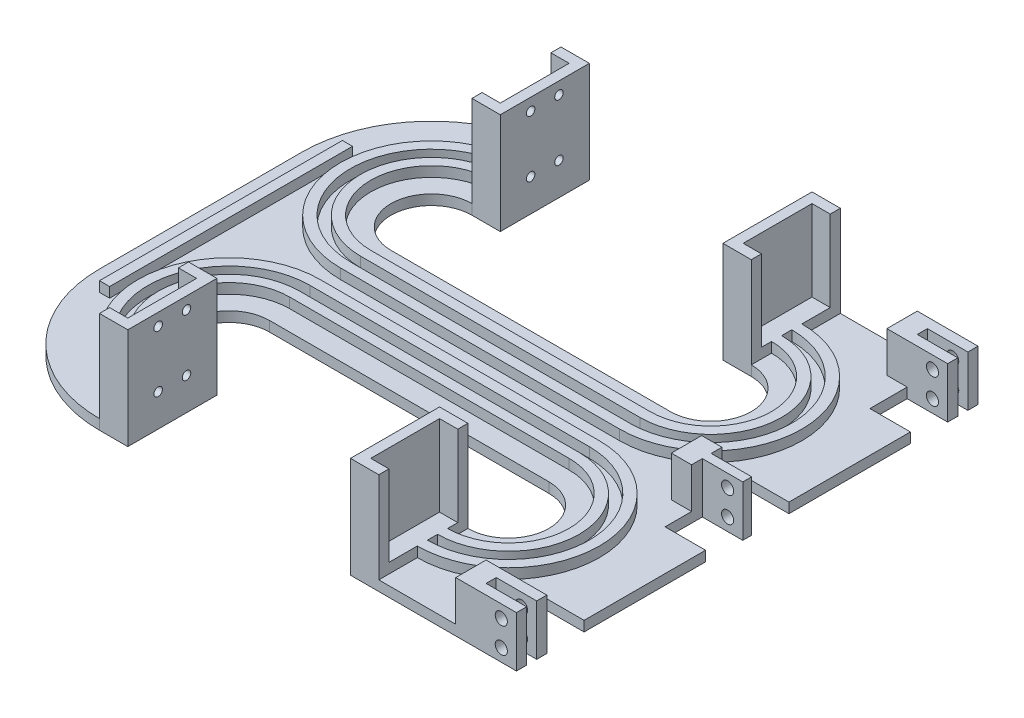
SolidWorks part; units mm, degrees
ref_plane "Front Plane" through (0, 0, 0) normal (0, 0, 1) x (1, 0, 0)
ref_plane "Top Plane" through (0, 0, 0) normal (0, 1, 0) x (1, 0, 0)
ref_plane "Right Plane" through (0, 0, 0) normal (1, 0, 0) x (0, 0, -1)
sketch "Sketch1" plane through (0, 0, 0) normal (0, 1, 0) x (1, 0, 0)
  line L5 (-62.5, 25) -> (-62.5, -25)
  line L6 (-30.5, -15) -> (38.5, -15)
  line L7 (38.5, -57) -> (62.5, -57)
  line L8 (62.5, -57) -> (62.5, 57)
  line L10 (-30.5, -57) -> (-30.5, 57) construction
  line L11 (-30.5, -35) -> (-23.5, -35)
  line L14 (-30.5, -57) -> (-23.5, -57)
  line L15 (-23.5, -35) -> (-23.5, -57)
  line L16 (38.5, -35) -> (31.5, -35)
  line L18 (38.5, -57) -> (31.5, -57)
  line L19 (31.5, -35) -> (31.5, -57)
  line L20 (38.5, -57) -> (38.5, 57) construction
  line L21 (-62.5, -25) -> (62.5, -25) construction
  line L22 (-62.5, 0) -> (62.5, 0) construction
  line L23 (-62.5, 25) -> (62.5, 25) construction
  line L24 (31.5, 35) -> (31.5, 57)
  line L25 (38.5, 57) -> (31.5, 57)
  line L26 (38.5, 35) -> (31.5, 35)
  line L27 (-23.5, 35) -> (-23.5, 57)
  line L28 (-30.5, 57) -> (-23.5, 57)
  line L29 (-30.5, 35) -> (-23.5, 35)
  line L30 (38.5, 57) -> (62.5, 57)
  line L31 (-30.5, 15) -> (38.5, 15)
  arc A0 (-62.5, -25) -> (-30.5, -57) centre (-30.5, -25) ccw
  arc A1 (-30.5, -15) -> (-30.5, -35) centre (-30.5, -25) ccw
  arc A2 (38.5, -15) -> (38.5, -35) centre (38.5, -25) cw
  arc A3 (38.5, 15) -> (38.5, 35) centre (38.5, 25) ccw
  arc A4 (-30.5, 15) -> (-30.5, 35) centre (-30.5, 25) cw
  arc A5 (-62.5, 25) -> (-30.5, 57) centre (-30.5, 25) cw
  point P23 (38.5, 0)
  point P24 (-30.5, 0)
  point P35 (0, 0)
  dimension "D2" = 10
  dimension "D1" = 25
  dimension "D3" = 22
  dimension "D4" = 7
  dimension "D5" = 55
  dimension "D6" = 125
extrude "Boss-Extrude1" add sketch "Sketch1" along normal blind 2.5
sketch "Sketch3" plane through (0, 2.5, 0) normal (0, 1, 0) x (1, 0, 0)
  line L0 (0, 0) -> (-62.5, 0) construction
  line L2 (-30.5, -2.5) -> (38.5, -2.5)
  line L3 (-30.5, -5) -> (38.5, -5)
  line L4 (-30.5, -7.5) -> (38.5, -7.5)
  line L5 (-30.5, -10) -> (38.5, -10)
  line L6 (-30.5, -15) -> (38.5, -15) construction
  line L7 (38.5, -35) -> (31.5, -35)
  line L8 (31.5, -35) -> (31.5, -57)
  line L9 (31.5, -57) -> (38.5, -57)
  line L10 (31.5, -57) -> (62.5, -57) construction
  line L11 (38.5, -57) -> (38.5, -47.5)
  line L12 (38.5, -42.5) -> (38.5, -45)
  line L13 (38.5, -35) -> (38.5, -40)
  line L14 (-30.5, -35) -> (-23.5, -35)
  line L15 (-23.5, -35) -> (-23.5, -57)
  line L16 (-23.5, -57) -> (-30.5, -57)
  line L17 (-30.5, -35) -> (-30.5, -40)
  line L18 (-30.5, -42.5) -> (-30.5, -45)
  line L19 (-30.5, -47.5) -> (-30.5, -57)
  line L20 (-62.5, 25) -> (-62.5, -25) construction
  line L21 (-57.5, 30) -> (-55, 30)
  line L23 (-57.5, 30) -> (-57.5, -30)
  line L24 (-57.5, -30) -> (-55, -30)
  line L25 (-55, 30) -> (-55, -30)
  line L26 (-30.5, 47.5) -> (-30.5, 57)
  line L27 (-30.5, 42.5) -> (-30.5, 45)
  line L28 (-30.5, 35) -> (-30.5, 40)
  line L29 (-23.5, 57) -> (-30.5, 57)
  line L30 (-23.5, 35) -> (-23.5, 57)
  line L31 (-30.5, 35) -> (-23.5, 35)
  line L32 (38.5, 35) -> (38.5, 40)
  line L33 (38.5, 42.5) -> (38.5, 45)
  line L34 (38.5, 57) -> (38.5, 47.5)
  line L35 (31.5, 57) -> (38.5, 57)
  line L36 (31.5, 35) -> (31.5, 57)
  line L37 (38.5, 35) -> (31.5, 35)
  line L38 (-30.5, 10) -> (38.5, 10)
  line L39 (-30.5, 7.5) -> (38.5, 7.5)
  line L40 (-30.5, 5) -> (38.5, 5)
  line L41 (-30.5, 2.5) -> (38.5, 2.5)
  arc A0 (38.5, -10) -> (38.5, -40) centre (38.5, -25) cw
  arc A1 (38.5, -7.5) -> (38.5, -42.5) centre (38.5, -25) cw
  arc A2 (38.5, -5) -> (38.5, -45) centre (38.5, -25) cw
  arc A3 (38.5, -2.5) -> (38.5, -47.5) centre (38.5, -25) cw
  arc A4 (-30.5, -10) -> (-30.5, -40) centre (-30.5, -25) ccw
  arc A5 (-30.5, -7.5) -> (-30.5, -42.5) centre (-30.5, -25) ccw
  arc A6 (-30.5, -5) -> (-30.5, -45) centre (-30.5, -25) ccw
  arc A7 (-30.5, -2.5) -> (-30.5, -47.5) centre (-30.5, -25) ccw
  arc A8 (-30.5, 2.5) -> (-30.5, 47.5) centre (-30.5, 25) cw
  arc A9 (-30.5, 5) -> (-30.5, 45) centre (-30.5, 25) cw
  arc A10 (-30.5, 7.5) -> (-30.5, 42.5) centre (-30.5, 25) cw
  arc A11 (-30.5, 10) -> (-30.5, 40) centre (-30.5, 25) cw
  arc A12 (38.5, 2.5) -> (38.5, 47.5) centre (38.5, 25) ccw
  arc A13 (38.5, 5) -> (38.5, 45) centre (38.5, 25) ccw
  arc A14 (38.5, 7.5) -> (38.5, 42.5) centre (38.5, 25) ccw
  arc A15 (38.5, 10) -> (38.5, 40) centre (38.5, 25) ccw
  point P49 (-62.5, 0)
  point P68 (-55, 0)
  point P69 (-57.5, 0)
  dimension "D1" = 2.5
  dimension "D2" = 2.5
  dimension "D3" = 2.5
  dimension "D4" = 5
  dimension "D5" = 30
  dimension "D6" = 2.5
  dimension "D7" = 5
extrude "Boss-Extrude2" add sketch "Sketch3" along normal blind 2.5
sketch "Sketch4" plane through (0, 5, 0) normal (0, 1, 0) x (1, 0, 0)
  line L0 (-30.5, -35) -> (-23.5, -35)
  line L1 (-23.5, -35) -> (-23.5, -57)
  line L2 (-23.5, -57) -> (-30.5, -57)
  line L3 (-30.5, -57) -> (-30.5, -54.5)
  line L4 (-30.5, -47.5) -> (-30.5, -57) construction
  line L5 (-30.5, -54.5) -> (-26, -54.5)
  line L6 (-26, -54.5) -> (-26, -37.5)
  line L7 (-26, -37.5) -> (-30.5, -37.5)
  line L8 (-30.5, -35) -> (-30.5, -40) construction
  line L9 (-30.5, -37.5) -> (-30.5, -35)
  line L10 (38.5, -35) -> (31.5, -35)
  line L11 (31.5, -35) -> (31.5, -57)
  line L12 (31.5, -35) -> (31.5, -57) construction
  line L13 (31.5, -57) -> (38.5, -57)
  line L14 (38.5, -57) -> (38.5, -54.5)
  line L15 (38.5, -57) -> (38.5, -47.5) construction
  line L16 (38.5, -54.5) -> (34, -54.5)
  line L17 (34, -54.5) -> (34, -37.5)
  line L18 (34, -37.5) -> (38.5, -37.5)
  line L19 (38.5, -40) -> (38.5, -35) construction
  line L20 (38.5, -37.5) -> (38.5, -35)
  line L21 (0, 0) -> (-62.5, 0) construction
  line L22 (-62.5, 25) -> (-62.5, -25) construction
  line L23 (38.5, 37.5) -> (38.5, 35)
  line L24 (34, 37.5) -> (38.5, 37.5)
  line L25 (34, 54.5) -> (34, 37.5)
  line L26 (38.5, 54.5) -> (34, 54.5)
  line L27 (38.5, 57) -> (38.5, 54.5)
  line L28 (31.5, 57) -> (38.5, 57)
  line L29 (31.5, 35) -> (31.5, 57)
  line L30 (38.5, 35) -> (31.5, 35)
  line L31 (-30.5, 37.5) -> (-30.5, 35)
  line L32 (-26, 37.5) -> (-30.5, 37.5)
  line L33 (-26, 54.5) -> (-26, 37.5)
  line L34 (-30.5, 54.5) -> (-26, 54.5)
  line L35 (-30.5, 57) -> (-30.5, 54.5)
  line L36 (-23.5, 57) -> (-30.5, 57)
  line L37 (-23.5, 35) -> (-23.5, 57)
  line L38 (-30.5, 35) -> (-23.5, 35)
  dimension "D1" = 2.5
  dimension "D2" = 2.5
  dimension "D3" = 2.5
extrude "Boss-Extrude3" add sketch "Sketch4" along normal blind 20
sketch "Sketch5" plane through (31.5, 0, 0) normal (-1, 0, 0) x (0, 0, 1)
  line L0 (35, 25) -> (57, 25) construction
  line L1 (57, 25) -> (57, 0) construction
  circle A0 centre (46, 12.5) radius 3.75
  point P4 (46, 25)
  point P7 (57, 12.5)
  dimension "D1" = 7.5
extrude "Boss-Extrude4" add sketch "Sketch5" along normal blind 5.5
sketch "Sketch6" plane through (31.5, 0, 0) normal (-1, 0, 0) x (0, 0, 1)
  line L0 (-57, 25) -> (-35, 25) construction
  line L1 (-57, 25) -> (-57, 0) construction
  circle A0 centre (-46, 12.5) radius 3.75
  point P4 (-46, 25)
  point P7 (-57, 12.5)
  dimension "D1" = 7.5
extrude "Boss-Extrude5" add sketch "Sketch6" along normal blind 5.5
sketch "Sketch8" plane through (-23.5, 0, 0) normal (1, 0, 0) x (0, 0, -1)
  line L0 (-35, 12.5) -> (-57, 12.5) construction
  line L1 (-35, 25) -> (-35, 0) construction
  line L2 (-57, 25) -> (-57, 0) construction
  line L3 (-35, 15) -> (-57, 15) construction
  line L4 (-46, 25) -> (-46, 0) construction
  line L5 (-57, 25) -> (-35, 25) construction
  line L6 (-57, 0) -> (-35, 0) construction
  circle A0 centre (-42.5, 22) radius 1.05
  circle A1 centre (-49.5, 22) radius 1.05
  circle A2 centre (-49.5, 8) radius 1.05
  circle A3 centre (-42.5, 8) radius 1.05
  dimension "D1" = 2.1
  dimension "D2" = 2.5
  dimension "D3" = 7
  dimension "D4" = 3.5
extrude "Cut-Extrude1" cut sketch "Sketch8" against normal blind 2.5
sketch "Sketch9" plane through (-23.5, 0, 0) normal (1, 0, 0) x (0, 0, -1)
  line L0 (57, 12.5) -> (35, 12.5) construction
  line L1 (57, 25) -> (57, 0) construction
  line L2 (35, 25) -> (35, 0) construction
  line L3 (46, 25) -> (46, 0) construction
  line L4 (35, 25) -> (57, 25) construction
  line L5 (35, 0) -> (57, 0) construction
  line L6 (57, 15) -> (35, 15) construction
  circle A0 centre (49.5, 22) radius 1.05
  circle A1 centre (42.5, 22) radius 1.05
  circle A2 centre (42.5, 8) radius 1.05
  circle A3 centre (49.5, 8) radius 1.05
  dimension "D2" = 2.1
  dimension "D1" = 2.5
  dimension "D3" = 7
  dimension "D4" = 3.5
extrude "Cut-Extrude2" cut sketch "Sketch9" against normal blind 2.5
sketch "Sketch10" plane through (0, 2.5, 0) normal (0, 1, 0) x (1, 0, 0)
  line L0 (62.5, -57) -> (62.5, 57) construction
  line L1 (62.5, 57) -> (57.5, 57)
  line L2 (62.5, 57) -> (62.5, 49.5)
  line L3 (62.5, 49.5) -> (57.5, 49.5)
  line L4 (57.5, 57) -> (57.5, 49.5)
  line L5 (62.5, 3.75) -> (57.5, 3.75)
  line L6 (62.5, 3.75) -> (62.5, -3.75)
  line L7 (62.5, -3.75) -> (57.5, -3.75)
  line L8 (57.5, 3.75) -> (57.5, -3.75)
  line L10 (62.5, -57) -> (57.5, -57)
  line L11 (62.5, -57) -> (62.5, -49.5)
  line L12 (62.5, -49.5) -> (57.5, -49.5)
  line L13 (57.5, -57) -> (57.5, -49.5)
  point P16 (62.5, 0)
  point P17 (62.5, 0)
  dimension "D1" = 7.5
  dimension "D2" = 5
extrude "Boss-Extrude6" add sketch "Sketch10" along normal blind 10
sketch "Sketch11" plane through (62.5, 0, 0) normal (1, 0, 0) x (0, 0, -1)
  line L0 (0, 12.5) -> (0, 0) construction
  line L1 (-3.75, 12.5) -> (3.75, 12.5) construction
  line L2 (-57, 0) -> (57, 0) construction
  line L3 (57, 12.5) -> (54.5, 12.5)
  line L4 (57, 12.5) -> (57, 0)
  line L5 (57, 0) -> (54.5, 0)
  line L6 (54.5, 12.5) -> (54.5, 0)
  line L7 (-1.1, 12.5) -> (1.1, 12.5)
  line L8 (49.5, 12.5) -> (52, 12.5)
  line L9 (49.5, 12.5) -> (49.5, 0)
  line L10 (49.5, 0) -> (52, 0)
  line L11 (52, 12.5) -> (52, 0)
  line L12 (1.1, 12.5) -> (1.1, 0)
  line L13 (1.1, 0) -> (-1.1, 0)
  line L14 (-1.1, 12.5) -> (-1.1, 0)
  line L15 (-52, 12.5) -> (-52, 0)
  line L16 (-49.5, 0) -> (-52, 0)
  line L17 (-49.5, 12.5) -> (-49.5, 0)
  line L18 (-49.5, 12.5) -> (-52, 12.5)
  line L19 (-54.5, 12.5) -> (-54.5, 0)
  line L20 (-57, 0) -> (-54.5, 0)
  line L21 (-57, 12.5) -> (-57, 0)
  line L22 (-57, 12.5) -> (-54.5, 12.5)
  dimension "D1" = 1.1
  dimension "D2" = 2.5
extrude "Boss-Extrude7" add sketch "Sketch11" along normal blind 10
sketch "Sketch12" plane through (0, 0, -57) normal (0, 0, -1) x (-1, 0, 0)
  line L0 (-72.5, 6.25) -> (-57.5, 6.25) construction
  line L1 (-72.5, 0) -> (-72.5, 12.5) construction
  line L2 (-57.5, 12.5) -> (-57.5, 2.5) construction
  line L3 (-65, 12.5) -> (-65, 6.25) construction
  line L4 (-72.5, 12.5) -> (-57.5, 12.5) construction
  line L5 (-65, 9.375) -> (-72.5, 9.375) construction
  circle A0 centre (-68.75, 9.375) radius 1.5
  circle A1 centre (-68.75, 3.125) radius 1.5
  dimension "D1" = 3
extrude "Cut-Extrude3" cut sketch "Sketch12" against normal blind 114
sketch "Sketch14" plane through (62.5, 0, 0) normal (1, 0, 0) x (0, 0, -1)
  line L0 (-49.5, 2.5) -> (-3.75, 2.5) construction
  line L1 (-40.3, 2.5) -> (-10.3, 2.5)
  line L2 (-40.3, 2.5) -> (-40.3, 0)
  line L3 (-40.3, 0) -> (-10.3, 0)
  line L4 (-10.3, 2.5) -> (-10.3, 0)
  line L5 (-49.5, 0) -> (-1.1, 0) construction
  line L6 (3.75, 2.5) -> (49.5, 2.5) construction
  line L7 (10.3, 2.5) -> (40.3, 2.5)
  line L8 (10.3, 2.5) -> (10.3, 0)
  line L9 (10.3, 0) -> (40.3, 0)
  line L10 (40.3, 2.5) -> (40.3, 0)
  line L11 (1.1, 0) -> (49.5, 0) construction
  point P8 (-25.3, 0)
  point P9 (-25.3, 0)
  point P18 (25.3, 0)
  point P19 (25.3, 0)
  dimension "D1" = 30
extrude "Boss-Extrude8" add sketch "Sketch14" along normal blind 10
